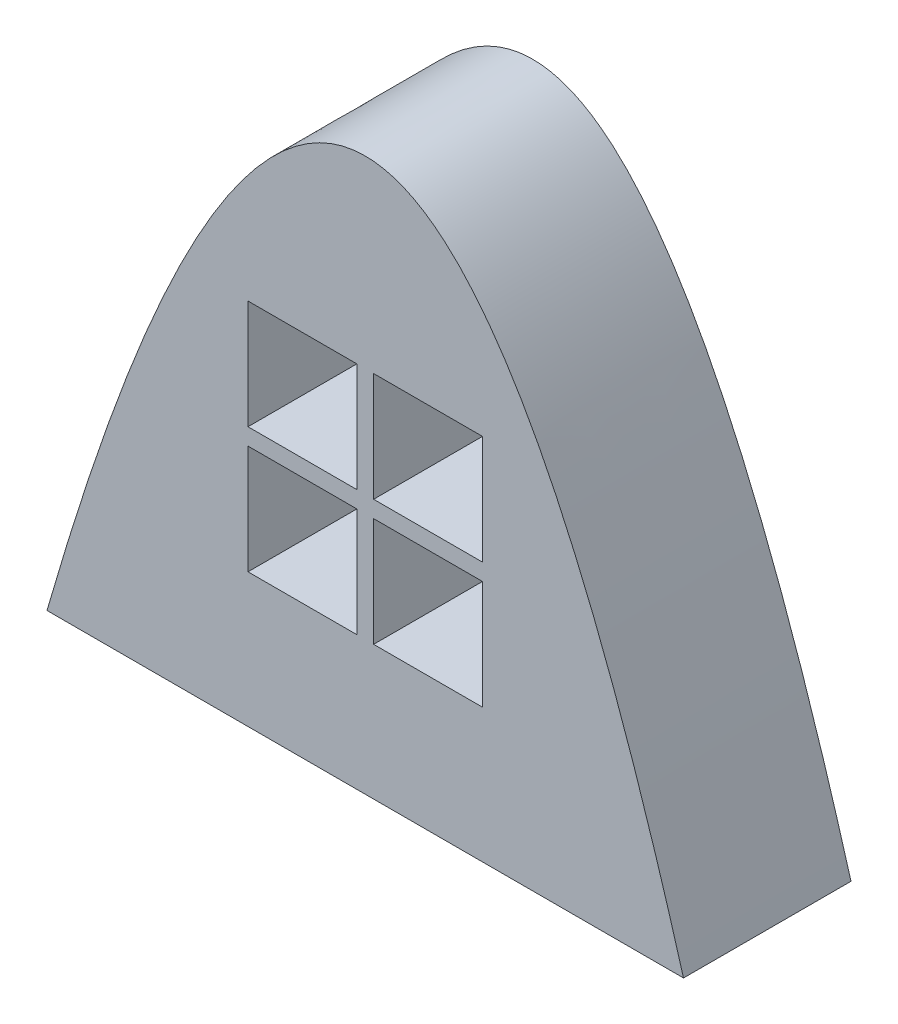
SolidWorks part; units mm, degrees
ref_plane "前视基准面" through (0, 0, 0) normal (0, 0, 1) x (1, 0, 0)
ref_plane "上视基准面" through (0, 0, 0) normal (0, 1, 0) x (1, 0, 0)
ref_plane "右视基准面" through (0, 0, 0) normal (1, 0, 0) x (0, 0, -1)
sketch "草图1" plane through (0, 0, 0) normal (0, 0, 1) x (1, 0, 0)
  line L0 (-19, 0) -> (19, 0)
  line L1 (0, 0) -> (0, 33)
  spline S0 degree 2 poles (-19, 0) (0, 66) (19, 0) knots 0 0 0 1 1 1
  point P4 (0, 0)
  dimension "D1" = 38
  dimension "D2" = 33
extrude "凸台-拉伸1" add sketch "草图1" along normal blind 10 contours S0 L0 L1 | S0 L1 L0
sketch "草图2" plane through (0, 0, 0) normal (0, 0, -1) x (-1, 0, 0)
  line L0 (19, 0) -> (-19, 0) construction
  line L1 (-7, 22) -> (7, 22)
  line L2 (-7, 22) -> (-7, 8)
  line L3 (-7, 8) -> (7, 8)
  line L4 (7, 22) -> (7, 8)
  line L5 (-7, 22) -> (7, 8) construction
  line L6 (-7, 8) -> (7, 22) construction
  line L7 (-7, 15) -> (7, 15)
  line L8 (0, 8) -> (0, 22)
  line L9 (-0.5, 7.9648) -> (-0.5, 22.0352)
  line L10 (0.5, 8) -> (0.5, 22)
  line L11 (-7, 15.5) -> (7, 15.5)
  line L12 (-7, 14.5) -> (7, 14.5)
  point P0 (0, 15)
  point P12 (0, 15)
  point P16 (0, 15)
  point P18 (-0.5, 15)
  point P21 (0.5, 15)
  point P24 (0, 15.5)
  point P27 (0, 14.5)
  dimension "D1" = 15
  dimension "D2" = 12
  dimension "D3" = 8
  dimension "D4" = 0.5
  dimension "D5" = 0.5
  dimension "D6" = 0.5
  dimension "D7" = 0.5
extrude "切除-拉伸1" cut sketch "草图2" against normal blind 10 contours L2 L11 L9 L1 | L12 L2 L3 L9 | L12 L10 L3 L4 | L10 L11 L4 L1
